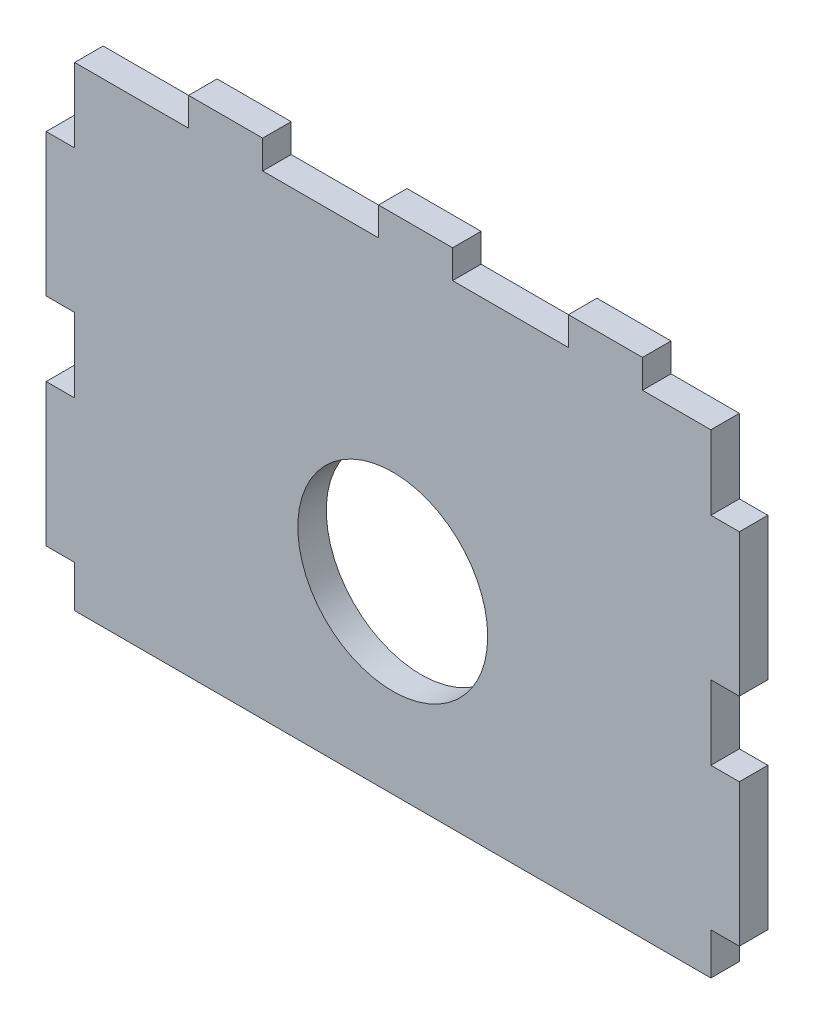
SolidWorks part; units mm, degrees
material "Oak"
ref_plane "Front Plane" through (0, 0, 0) normal (0, 0, 1) x (1, 0, 0)
ref_plane "Top Plane" through (0, 0, 0) normal (0, 1, 0) x (1, 0, 0)
ref_plane "Right Plane" through (0, 0, 0) normal (1, 0, 0) x (0, 0, -1)
sketch "Sketch1" plane through (0, 0, 0) normal (0, 0, 1) x (1, 0, 0)
  line L1 (-40.9935, 16.542) -> (32.0065, 16.542)
  line L2 (-40.9935, 16.542) -> (-40.9935, -33.458)
  line L3 (-40.9935, -33.458) -> (32.0065, -33.458)
  line L4 (32.0065, 16.542) -> (32.0065, -33.458)
  dimension "D1" = 50
  dimension "D2" = 73
extrude "Boss-Extrude1" add sketch "Sketch1" along normal blind 3
sketch "Sketch2" plane through (0, 0, 3) normal (0, 0, 1) x (1, 0, 0)
  line L12 (-40.9935, 16.542) -> (-37.9935, 16.542)
  line L13 (-40.9935, 16.542) -> (-40.9935, 8.742)
  line L14 (-40.9935, 8.742) -> (-37.9935, 8.742)
  line L15 (-37.9935, 16.542) -> (-37.9935, 8.742)
  dimension "D1" = 7.8
  dimension "D2" = 3
extrude "Cut-Extrude1" cut sketch "Sketch2" against normal through all
pattern_linear "LPattern1" count 3 spacing 22.8 along (0, -1, 0) of "Cut-Extrude1"
sketch "Sketch3" plane through (0, 0, 3) normal (0, 0, 1) x (1, 0, 0)
  line L0 (32.0065, 16.542) -> (-37.9935, 16.542) construction
  line L1 (29.0065, 16.542) -> (32.0065, 16.542)
  line L2 (29.0065, 16.542) -> (29.0065, 8.742)
  line L3 (29.0065, 8.742) -> (32.0065, 8.742)
  line L4 (32.0065, 16.542) -> (32.0065, 8.742)
  line L5 (32.0065, -33.458) -> (32.0065, 16.542) construction
  point P8 (30.5065, 16.542)
  dimension "D1" = 7.8
  dimension "D2" = 3
extrude "Cut-Extrude2" cut sketch "Sketch3" against normal through all
pattern_linear "LPattern2" count 4 spacing 22.8 along (0, -1, 0) of "Cut-Extrude2"
sketch "Sketch6" plane through (0, 0, 3) normal (0, 0, 1) x (1, 0, 0)
  line L0 (-37.9935, -33.458) -> (29.0065, -33.458) construction
  line L1 (-40.9935, -14.058) -> (-37.9935, -14.058)
  line L2 (-40.9935, -14.058) -> (-40.9935, -33.458)
  line L3 (-40.9935, -33.458) -> (-37.9935, -33.458)
  line L4 (-37.9935, -14.058) -> (-37.9935, -33.458)
  dimension "D1" = 3
extrude "Cut-Extrude3" cut sketch "Sketch6" against normal blind 10
sketch "Sketch7" plane through (0, 16.542, 0) normal (0, 1, 0) x (1, 0, 0)
  line L0 (29.0065, 0) -> (-37.9935, 0) construction
  line L1 (-25.9935, 0) -> (-18.1935, 0)
  line L2 (-25.9935, 0) -> (-25.9935, -3)
  line L3 (-25.9935, -3) -> (-18.1935, -3)
  line L4 (-18.1935, 0) -> (-18.1935, -3)
  line L5 (29.0065, -3) -> (-37.9935, -3) construction
  line L6 (-37.9935, 0) -> (-37.9935, -3) construction
  dimension "D1" = 12
  dimension "D2" = 7.8
extrude "Boss-Extrude2" add sketch "Sketch7" along normal blind 3
pattern_linear "LPattern3" count 3 spacing 20 along (1, 0, 0) of "Boss-Extrude2"
sketch "Sketch8" plane through (-37.9935, 0, 0) normal (-1, 0, 0) x (0, 0, 1)
  line L0 (0, -33.458) -> (0, -6.258) construction
  line L1 (0, -14.058) -> (3, -14.058)
  line L2 (0, -14.058) -> (0, -29.058)
  line L3 (0, -29.058) -> (3, -29.058)
  line L4 (3, -14.058) -> (3, -29.058)
  line L5 (3, -33.458) -> (3, -6.258) construction
  line L6 (0, -6.258) -> (3, -6.258) construction
  dimension "D1" = 7.8
  dimension "D2" = 15
extrude "Boss-Extrude3" add sketch "Sketch8" along normal blind 3
sketch "Sketch9" plane through (0, 0, 3) normal (0, 0, 1) x (1, 0, 0)
  line L4 (-40.9935, -14.058) -> (-37.9935, -14.058) construction
  line L5 (-37.9935, 13.5275) -> (29.0065, 13.5275) construction
  line L6 (-37.9935, 8.742) -> (-37.9935, 16.542) construction
  line L7 (29.0065, 16.542) -> (29.0065, 8.742) construction
  circle A0 centre (-4.4935, -14.058) radius 10
  point P2 (0, 0)
  point P7 (-4.4935, 13.5275)
  dimension "D1" = 20
extrude "Cut-Extrude4" cut sketch "Sketch9" against normal up to next
